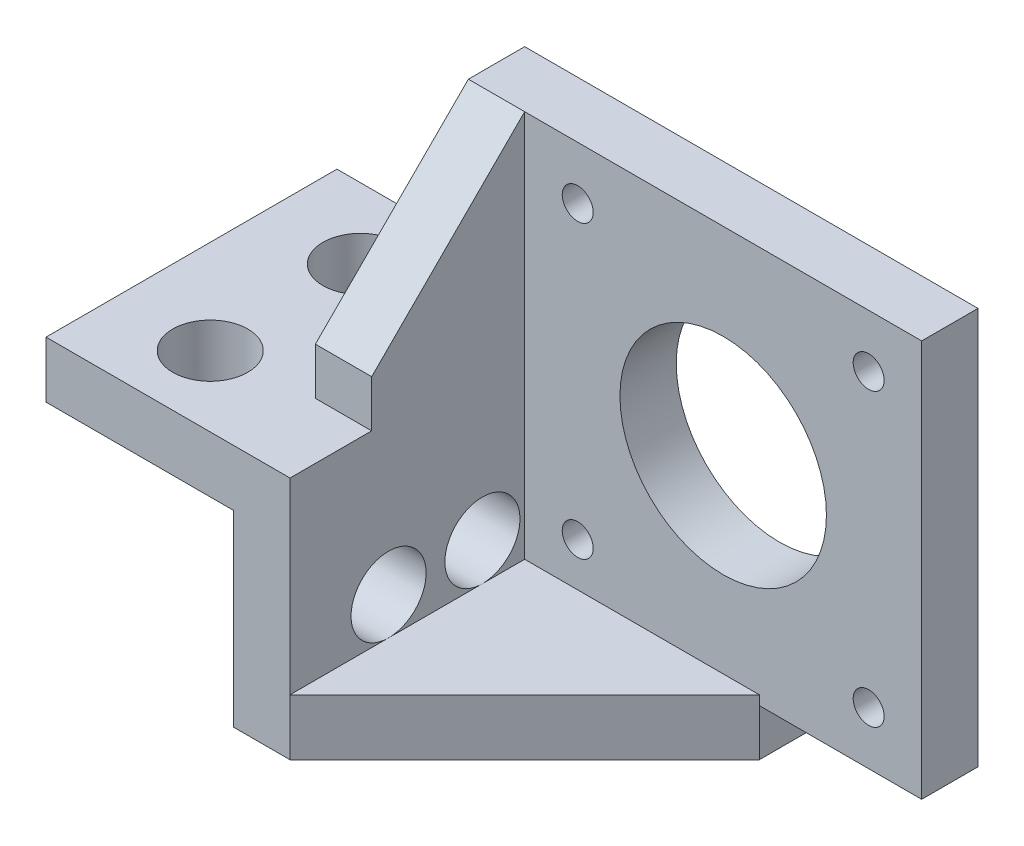
SolidWorks part; units mm, degrees
ref_plane "Front Plane" through (0, 0, 0) normal (1, 0, 0) x (0, 1, 0)
ref_plane "Top Plane" through (0, 0, 0) normal (0, 0, 1) x (0, 1, 0)
ref_plane "Right Plane" through (0, 0, 0) normal (0, 1, 0) x (-1, 0, 0)
sketch "Sketch2" plane through (0, 0, 0) normal (0, 0, 1) x (0, 1, 0)
  line L1 (0, 0) -> (20, 0)
  line L2 (0, 0) -> (0, -20)
  line L3 (0, -20) -> (20, -20)
  line L4 (20, 0) -> (20, -20)
  line L5 (0, 0) -> (26, 0)
  line L6 (0, 0) -> (0, -26)
  line L7 (0, -26) -> (26, -26)
  line L8 (26, 0) -> (26, -26)
  dimension "D1" = 20
  dimension "D2" = 20
  dimension "D3" = 6
  dimension "D4" = 6
extrude "Boss-Extrude3" add sketch "Sketch2" along normal blind 31 separate body contours L8 L5 L4 L3 L6 L7
sketch "Sketch3" plane through (0, 0, 0) normal (0, 0, -1) x (1, 0, 0)
  line L0 (26, 0) -> (26, -26) construction
  line L1 (26, -5) -> (68.3, -5)
  line L2 (26, -5) -> (26, -47.3)
  line L3 (26, -47.3) -> (68.3, -47.3)
  line L4 (68.3, -5) -> (68.3, -47.3)
  line L5 (47.15, -47.3) -> (47.15, -5) construction
  line L6 (26, -26.15) -> (68.3, -26.15) construction
  line L7 (20, 0) -> (26, 0) construction
  line L8 (62.65, -41.65) -> (31.65, -41.65) construction
  line L9 (62.65, -41.65) -> (62.65, -10.65) construction
  line L10 (62.65, -10.65) -> (31.65, -10.65) construction
  line L11 (31.65, -41.65) -> (31.65, -10.65) construction
  line L12 (62.65, -41.65) -> (31.65, -10.65) construction
  line L13 (62.65, -10.65) -> (31.65, -41.65) construction
  circle A0 centre (47.15, -26.15) radius 11
  circle A1 centre (31.65, -10.65) radius 1.65
  circle A2 centre (62.65, -10.65) radius 1.65
  circle A3 centre (62.65, -41.65) radius 1.65
  circle A4 centre (31.65, -41.65) radius 1.65
  point P16 (62.65, -14.6162)
  point P240 (47.15, -26.15)
  line M9 (26, -26) -> (26, 0)
  dimension "D2" = 3.3
  dimension "D3" = 22
  dimension "D1" = 42.3
  dimension "D4" = 31
  dimension "D5" = 5
extrude "Boss-Extrude4" add sketch "Sketch3" against normal blind 6 contours L4 L1 L2 L3 A4 A3 A2 A1 A0 M9
sketch "Sketch4" plane through (0, 20, 0) normal (0, -1, 0) x (1, 0, 0)
  line L0 (10, 31) -> (10, 0) construction
  line L1 (0, 31) -> (20, 31) construction
  line L2 (0, 0) -> (20, 0) construction
  line L3 (20, 15.5) -> (0, 15.5) construction
  line L4 (20, 31) -> (20, 0) construction
  line L5 (0, 31) -> (0, 0) construction
  circle A0 centre (10, 7.5) radius 4
  circle A1 centre (10, 23.5) radius 4
  point P10 (10, 15.5)
  dimension "D1" = 8
  dimension "D2" = 8
  dimension "D3" = 8
extrude "Cut-Extrude1" cut sketch "Sketch4" against normal up to surface (6 mm away) up to face at (15.6, 26, 13.6)
sketch "Sketch7" plane through (20, 0, 0) normal (-1, 0, 0) x (0, -1, 0)
  line L0 (-10, 31) -> (-10, 0) construction
  line L1 (0, 31) -> (-20, 31) construction
  line L2 (0, 0) -> (-20, 0) construction
  line L3 (-20, 15.5) -> (0, 15.5) construction
  line L4 (-20, 31) -> (-20, 0) construction
  line L5 (0, 31) -> (0, 0) construction
  circle A0 centre (-10, 20.5) radius 4
  circle A1 centre (-10, 10.5) radius 4
  point P16 (0, 0)
  point P17 (-10, 15.5)
  dimension "D2" = 8
  dimension "D1" = 5
  dimension "D3" = 5
extrude "Cut-Extrude2" cut sketch "Sketch7" against normal through all contours A0 | A1
sketch "Sketch10" plane through (26, 0, 0) normal (-1, 0, 0) x (0, -1, 0)
  line L0 (-26, 0) -> (-47.3, 0)
  line L1 (-47.3, 0) -> (-47.3, 6)
  line L2 (-47.3, 6) -> (-26, 6)
  line L3 (-26, 6) -> (-26, 0)
  line L4 (-26, 0) -> (-26, 22.3)
  line L5 (-26, 22.3) -> (-31, 22.3)
  line L6 (-31, 22.3) -> (-47.3, 6)
  line M3 (-26, 0) -> (-26, 6)
  line M4 (-26, 6) -> (-47.3, 6)
  line M5 (-47.3, 6) -> (-47.3, 0)
  line M6 (-47.3, 0) -> (-26, 0)
  dimension "D1" = 45
  dimension "D2" = 5
extrude "Boss-Extrude6" add sketch "Sketch10" along normal blind 6 contours M6 M3 M4 M5 | L5 L6 L4 M4
sketch "Sketch11" plane through (0, 5, 0) normal (0, -1, 0) x (1, 0, 0)
  line L0 (26, 6) -> (26, 0)
  line L1 (26, 6) -> (26, 0) construction
  line L2 (26, 0) -> (68.3, 0)
  line L3 (68.3, 0) -> (68.3, 6)
  line L4 (68.3, 6) -> (26, 6)
  line L5 (26, 0) -> (26, 31)
  line L6 (26, 31) -> (51, 6)
  line L7 (51, 6) -> (51, 0)
  line M6 (26, 0) -> (68.3, 0)
  line M9 (26, 6) -> (26, 0)
  dimension "D1" = 45
extrude "Boss-Extrude7" add sketch "Sketch11" along normal blind 5 contours L6 L5 L4 | L7 L4 M9 M6
sketch "Sketch13" plane through (0, 5, 0) normal (0, 1, 0) x (-1, 0, 0)
  line L0 (-51, 6) -> (-26, 31)
  line L1 (-26, 31) -> (-26, 6)
  line L2 (-26, 6) -> (-51, 6)
extrude "Boss-Extrude8" add sketch "Sketch13" along normal blind 1
equation "\"extrusion_width\"= 20mm"
equation "\"frame_height\"= 360mm"
equation "\"frame_width\"= 320mm"
equation "\"frame_length\"= 320mm"
equation "\"bed_radius\"= 100mm"
equation "\"D1@Sketch2\"=\"extrusion_width\""
equation "\"D2@Sketch2\"=\"extrusion_width\""
equation "\"D4@Sketch2\"=\"D3@Sketch2\""
equation "\"D3@Sketch4\"=\"D2@Sketch4\""
equation "\"hole_for_extrusion\"= 8mm"
equation "\"D2@Sketch7\"=\"hole_for_extrusion\""
equation "\"D3@Sketch7\"=\"D1@Sketch7\""
equation "\"cantilever_support_thickness\"= 5mm"
equation "\"D5@Sketch3\"=\"cantilever_support_thickness\""
equation "\"D1@Boss-Extrude7\"=\"cantilever_support_thickness\""
